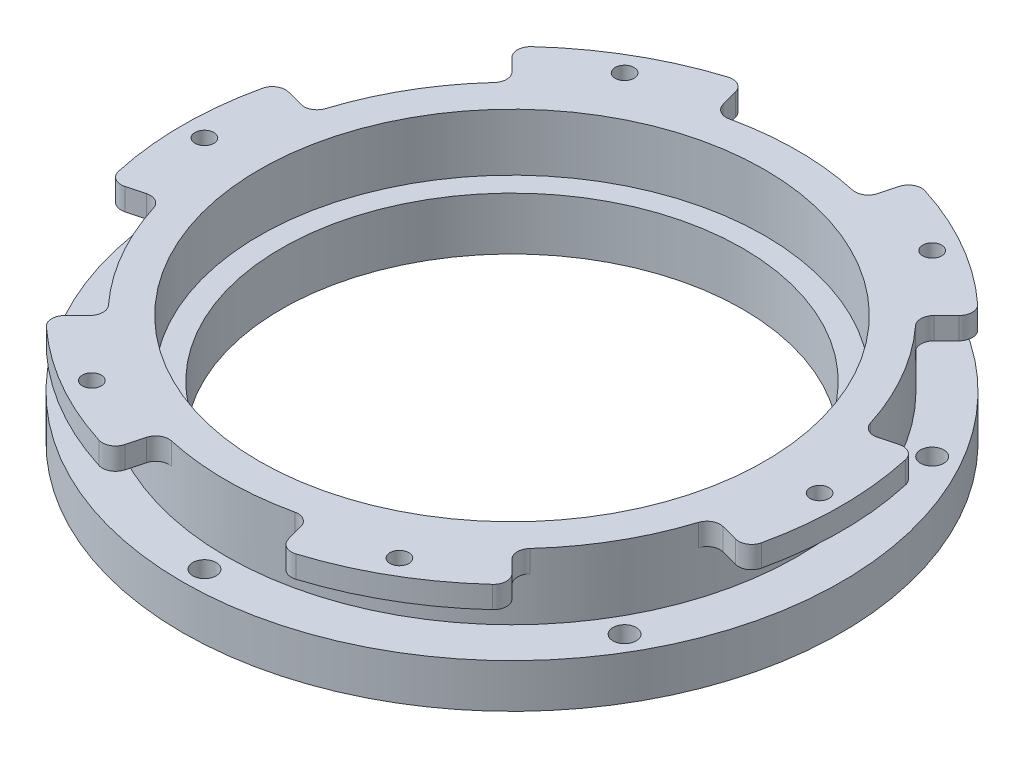
SolidWorks part; units mm, degrees
material "ABS"
ref_plane "前视基准面" through (0, 0, 0) normal (0, 0, 1) x (1, 0, 0)
ref_plane "上视基准面" through (0, 0, 0) normal (0, 1, 0) x (1, 0, 0)
ref_plane "右视基准面" through (0, 0, 0) normal (1, 0, 0) x (0, 0, -1)
other "Configuration Table"
sketch "草图1" plane through (0, 0, 0) normal (0, 1, 0) x (1, 0, 0)
  circle A0 centre (0, 0) radius 75
  circle A1 centre (0, 0) radius 70 construction
  circle A2 centre (0, 70) radius 2.65
  circle A3 centre (60.6218, 35) radius 2.65
  circle A4 centre (60.6218, -35) radius 2.65
  circle A5 centre (0, -70) radius 2.65
  circle A6 centre (-60.6218, -35) radius 2.65
  circle A7 centre (-60.6218, 35) radius 2.65
  point P18 (0, 0)
  dimension "D1" = 150
  dimension "D2" = 140
  dimension "D3" = 5.3
  dimension "D4" = 6
extrude "凸台-拉伸1" add sketch "草图1" along normal blind 10
sketch "草图2" plane through (0, 10, 0) normal (0, 1, 0) x (1, 0, 0)
  circle A0 centre (0, 0) radius 65
  circle A1 centre (0, 0) radius 52.5
  dimension "D1" = 105
  dimension "D2" = 130
extrude "凸台-拉伸2" add sketch "草图2" along normal blind 2
sketch "草图3" plane through (0, 12, 0) normal (0, 1, 0) x (1, 0, 0)
  circle A0 centre (0, 0) radius 65
  circle A1 centre (0, 0) radius 57.5
  dimension "D1" = 130
  dimension "D2" = 115
extrude "凸台-拉伸3" add sketch "草图3" along normal blind 13
sketch "草图4" plane through (0, 25, 0) normal (0, 1, 0) x (1, 0, 0)
  line L1 (-53.033, 53.033) -> (-45.9619, 45.9619)
  line L2 (-16.8232, 62.7852) -> (-19.4114, 72.4444)
  line L3 (0, 0) -> (-37.5, 64.9519) construction
  arc A0 (-19.4114, 72.4444) -> (-53.033, 53.033) centre (0, 0) ccw
  arc A1 (-16.8232, 62.7852) -> (-45.9619, 45.9619) centre (0, 0) ccw
  circle A2 centre (0, 0) radius 70 construction
  circle A3 centre (-35, 60.6218) radius 2.15
  dimension "D1" = 130
  dimension "D2" = 150
  dimension "D3" = 140
  dimension "D6" = 4.3
  dimension "D4" = 30
  dimension "D5" = 15
extrude "凸台-拉伸4" add sketch "草图4" against normal blind 5
pattern_circular "阵列(圆周)1" count 6 over 360 about axis through (0, 0, 0) along (0, 1, 0) of "凸台-拉伸4"
fillet "圆角1" radius 3 24 edges at (-45.9619, 22.5, -45.9619) (-53.033, 22.5, -53.033) (-19.4114, 22.5, -72.4444) (-16.8232, 22.5, -62.7852) (16.8232, 22.5, -62.7852) (19.4114, 22.5, -72.4444) (53.033, 22.5, -53.033) (45.9619, 22.5, -45.9619) (62.7852, 22.5, -16.8232) (72.4444, 22.5, -19.4114) (72.4444, 22.5, 19.4114) (62.7852, 22.5, 16.8232) (53.033, 22.5, 53.033) (19.4114, 22.5, 72.4444) (-16.8232, 22.5, 62.7852) (-19.4114, 22.5, 72.4444) (-53.033, 22.5, 53.033) (-45.9619, 22.5, 45.9619) (-62.7852, 22.5, 16.8232) (-72.4444, 22.5, 19.4114) (-72.4444, 22.5, -19.4114) (-62.7852, 22.5, -16.8232) (16.8232, 22.5, 62.7852) (45.9619, 22.5, 45.9619)
sketch "草图6" plane through (0, 10, 0) normal (0, 1, 0) x (1, 0, 0)
  circle A0 centre (0, 0) radius 52.5
  dimension "D1" = 105
extrude "切除-拉伸1" cut sketch "草图6" against normal blind 80
